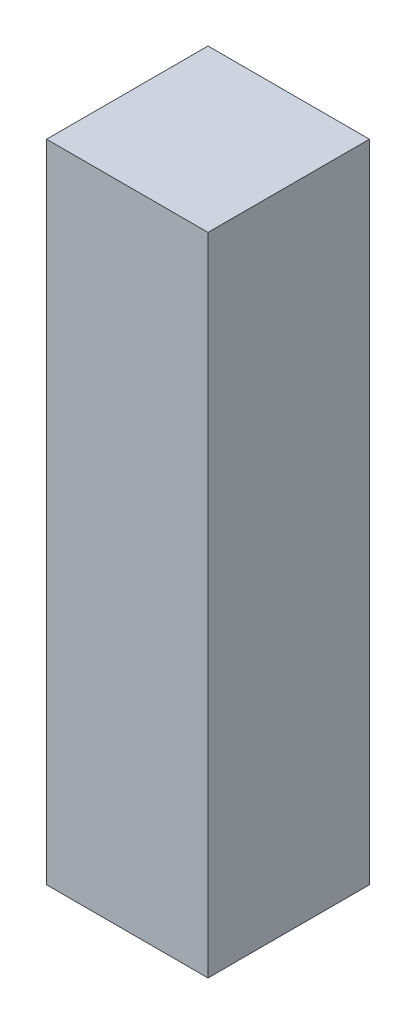
SolidWorks part; units mm, degrees
ref_plane "Front Plane" through (0, 0, 0) normal (0, 0, 1) x (1, 0, 0)
ref_plane "Top Plane" through (0, 0, 0) normal (0, 1, 0) x (1, 0, 0)
ref_plane "Right Plane" through (0, 0, 0) normal (1, 0, 0) x (0, 0, -1)
sketch "Sketch1" plane through (0, 0, 0) normal (0, 1, 0) x (1, 0, 0)
  line L1 (19.05, -19.05) -> (-19.05, -19.05)
  line L2 (19.05, -19.05) -> (19.05, 19.05)
  line L3 (19.05, 19.05) -> (-19.05, 19.05)
  line L4 (-19.05, -19.05) -> (-19.05, 19.05)
  line L5 (19.05, -19.05) -> (-19.05, 19.05) construction
  line L6 (19.05, 19.05) -> (-19.05, -19.05) construction
  point P0 (0, 0)
  dimension "D1" = 38.1
  dimension "D2" = 38.1
extrude "Boss-Extrude1" add sketch "Sketch1" along normal blind 152.4
